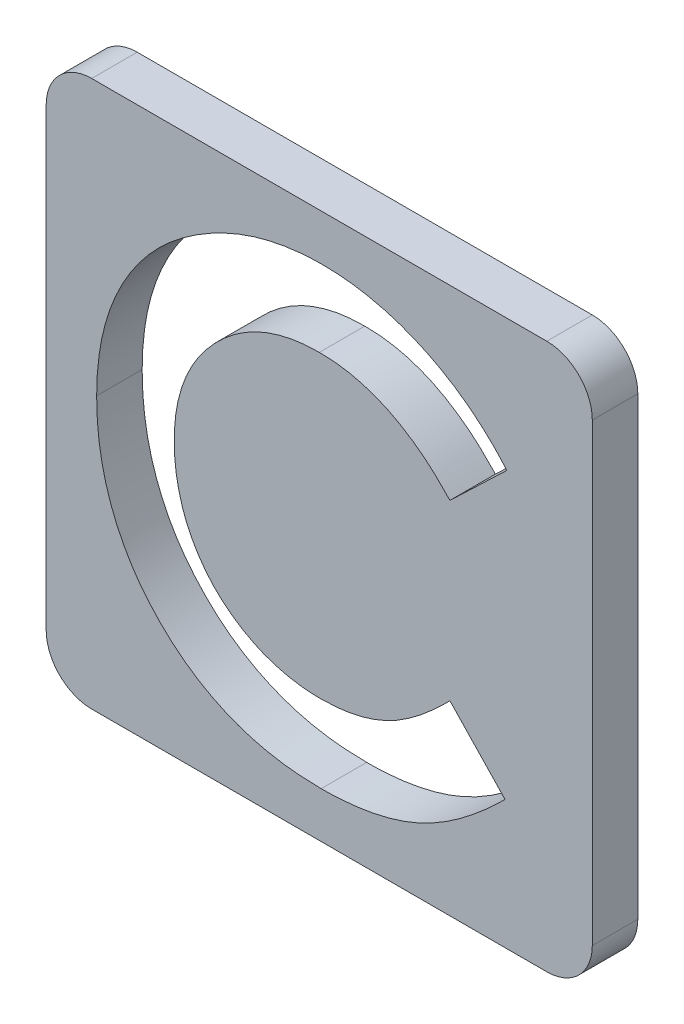
SolidWorks part; units mm, degrees
ref_plane "Front Plane" through (0, 0, 0) normal (0, 0, 1) x (1, 0, 0)
ref_plane "Top Plane" through (0, 0, 0) normal (0, 1, 0) x (1, 0, 0)
ref_plane "Right Plane" through (0, 0, 0) normal (1, 0, 0) x (0, 0, -1)
sketch "Sketch1" plane through (0, 0, 0) normal (0, 0, 1) x (1, 0, 0)
  line L1 (-50, 60) -> (50, 60)
  line L2 (-60, 50) -> (-60, -50)
  line L3 (-50, -60) -> (50, -60)
  line L4 (60, 50) -> (60, -50)
  line L5 (-60, 60) -> (60, -60) construction
  line L6 (-60, -60) -> (60, 60) construction
  arc A0 (-60, -50) -> (-50, -60) centre (-50, -50) ccw
  arc A1 (50, -60) -> (60, -50) centre (50, -50) ccw
  arc A2 (50, 60) -> (60, 50) centre (50, 50) cw
  arc A3 (-50, 60) -> (-60, 50) centre (-50, 50) ccw
  point P0 (0, 0)
  dimension "D3" = 10
  dimension "D1" = 120
  dimension "D2" = 120
extrude "Boss-Extrude1" add sketch "Sketch1" along normal blind 10 contours A3 L2 A0 L3 A1 L4 A2 L1
sketch "Sketch2" plane through (0, 0, 10) normal (0, 0, 1) x (1, 0, 0)
  line L0 (0, 0) -> (0, 40) construction
  line L1 (-50, 50) -> (50, 50) construction
  line L2 (-50, 50) -> (-50, -50) construction
  line L3 (-50, -50) -> (50, -50) construction
  line L4 (50, 50) -> (50, -50) construction
  line L5 (-50, 50) -> (50, -50) construction
  line L6 (-50, -50) -> (50, 50) construction
  line L7 (0, 40) -> (-40, 40) construction
  line L8 (-40, 40) -> (-40, 0) construction
  line L9 (-40, 0) -> (0, 0) construction
  line L11 (0, 20) -> (-20, 20) construction
  line L12 (-20, 40) -> (-20, 20) construction
  circle A0 centre (0, 40) radius 4 construction
  circle A1 centre (0, 20) radius 4 construction
  circle A2 centre (0, 0) radius 4 construction
  circle A3 centre (-20, 20) radius 4 construction
  circle A4 centre (-20, 40) radius 4 construction
  circle A5 centre (-40, 40) radius 4 construction
  circle A6 centre (0, 0) radius 4 construction
  circle A7 centre (20, 0) radius 4 construction
  circle A8 centre (40, 0) radius 4 construction
  circle A9 centre (40, 20) radius 4 construction
  circle A10 centre (40, 40) radius 4 construction
  circle A11 centre (20, 20) radius 4 construction
  circle A12 centre (0, 0) radius 4 construction
  circle A13 centre (0, -20) radius 4 construction
  circle A14 centre (0, -40) radius 4 construction
  circle A15 centre (20, -40) radius 4 construction
  circle A16 centre (40, -40) radius 4 construction
  circle A17 centre (20, -20) radius 4 construction
  circle A18 centre (0, 0) radius 4 construction
  circle A19 centre (-20, 0) radius 4 construction
  circle A20 centre (-40, 0) radius 4 construction
  circle A21 centre (-40, -20) radius 4 construction
  circle A22 centre (-40, -40) radius 4 construction
  circle A23 centre (-20, -20) radius 4 construction
  text T0 "C" font "Century Gothic" height 95
  point P0 (0, 0)
  point P55 (0, 0)
  dimension "D4" = 8
  dimension "D1" = 100
  dimension "D2" = 100
  dimension "D3" = 40
  dimension "D5" = 4
extrude "Cut-Extrude16" cut sketch "Sketch2" against normal blind 10
